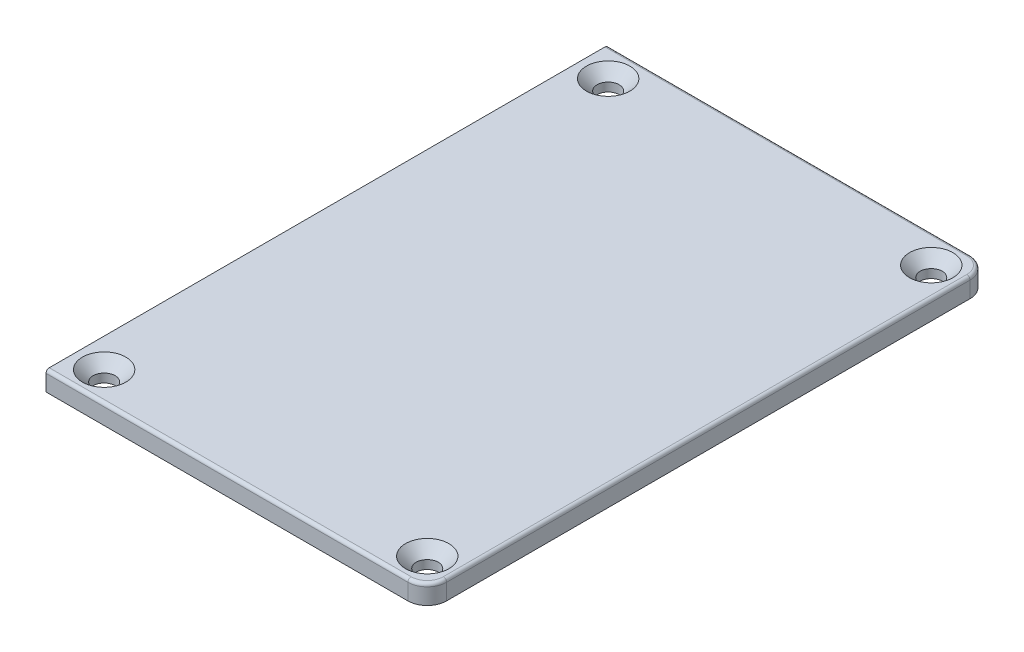
SolidWorks part; units mm, degrees
ref_plane "Front Plane" through (0, 0, 0) normal (0, 0, 1) x (1, 0, 0)
ref_plane "Top Plane" through (0, 0, 0) normal (0, 1, 0) x (1, 0, 0)
ref_plane "Right Plane" through (0, 0, 0) normal (1, 0, 0) x (0, 0, -1)
sketch "Sketch1" plane through (0, 0, 0) normal (0, 1, 0) x (1, 0, 0)
  line L1 (-29.5, -43.5) -> (29.5, -43.5)
  line L2 (-29.5, -43.5) -> (-29.5, 43.5)
  line L3 (-29.5, 43.5) -> (29.5, 43.5)
  line L4 (29.5, -43.5) -> (29.5, 43.5)
  line L5 (-29.5, -43.5) -> (29.5, 43.5) construction
  line L6 (-29.5, 43.5) -> (29.5, -43.5) construction
  point P0 (0, 0)
  dimension "D1" = 59
  dimension "D2" = 87
extrude "Boss-Extrude1" add sketch "Sketch1" along normal mid plane 3
sketch "Sketch2" plane through (0, 1.5, 0) normal (0, 1, 0) x (1, 0, 0)
  line L0 (-29.5, 43.5) -> (-29.5, -43.5) construction
  line L1 (29.5, 43.5) -> (-29.5, 43.5) construction
  line L2 (-29.5, -43.5) -> (29.5, -43.5) construction
  line L3 (29.5, -43.5) -> (29.5, 43.5) construction
  point P0 (-25, 39)
  point P1 (25, 39)
  point P2 (25, -39)
  point P3 (-25, -39)
  dimension "D1" = 4.5
  dimension "D2" = 4.5
  dimension "D3" = 4.5
  dimension "D4" = 4.5
hole_wizard "CSK for M3 SFHCS1" positions "Sketch3" profile "Sketch4" countersink size "M3" standard "ANSI Metric" end condition through all
sketch "Sketch3" plane through (0, 1.5, 0) normal (0, 1, 0) x (1, 0, 0)
  point P0 (-25, 39)
  point P3 (-25, -39)
  point P6 (25, -39)
  point P9 (25, 39)
sketch "Sketch4" plane through (-25, 1.5, -39) normal (1, 0, 0) x (0, 0, 1)
  line L0 (0, 0) -> (0, 3)
  line L1 (0, 3) -> (1.7, 3)
  line L2 (1.7, 3) -> (1.7, 1.66)
  line L3 (1.7, 1.66) -> (3.36, 0)
  line L5 (3.36, 0) -> (0, 0)
  line L6 (-1.7, 1.66) -> (-3.36, 0) construction
  line L11 (0, -6.35) -> (0, 107.95) construction
  dimension "Thru Hole Dia." = 3.4
  dimension "Thru Hole Depth" = 3
  dimension "Near C'Sink Dia." = 6.72
  dimension "Near C'Sink Angle" = 90
fillet "Fillet3" radius 3 2 edges at (29.5, 0, -43.5) (29.5, 0, 43.5)
fillet "Fillet4" radius 0.5 5 edges at (-1.5, 1.5, 43.5) (28.6213, 1.5, 42.6213) (-1.5, 1.5, -43.5) (28.6213, 1.5, -42.6213) (29.5, 1.5, 0)
equation "\"D2@Sketch2\"=\"D1@Sketch2\""
equation "\"D3@Sketch2\"=\"D1@Sketch2\""
equation "\"D4@Sketch2\"=\"D1@Sketch2\""
